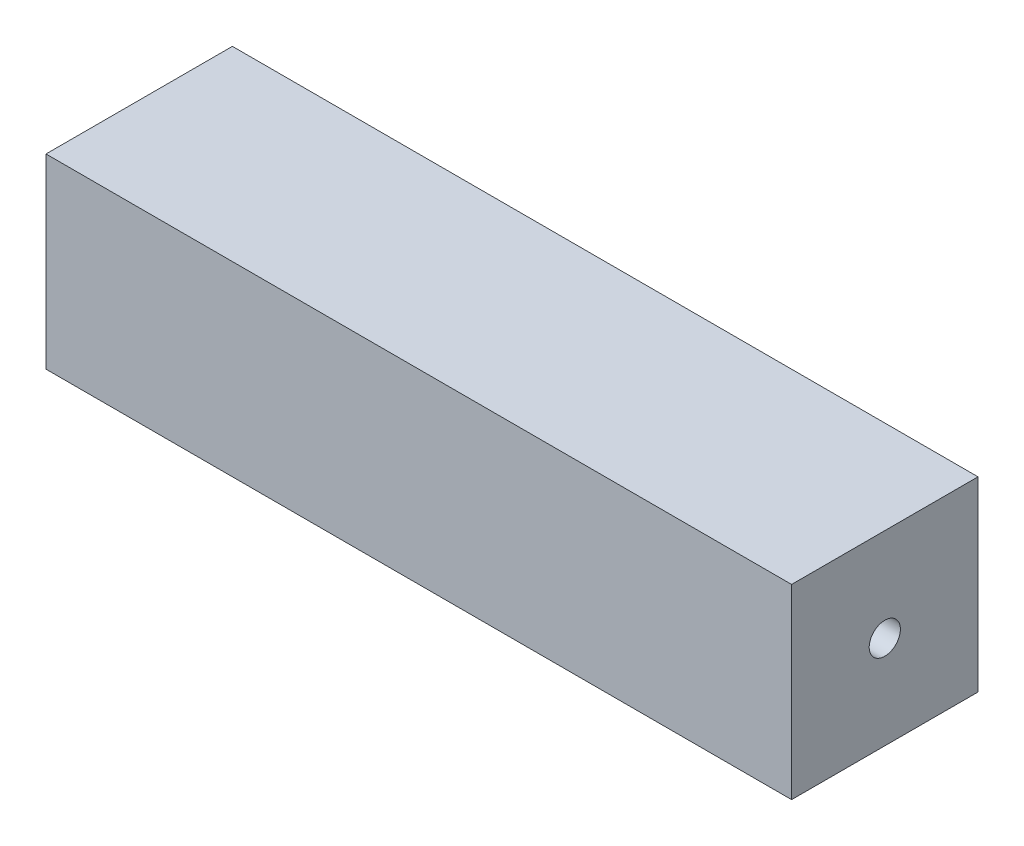
SolidWorks part; units mm, degrees
ref_plane "Front Plane" through (0, 0, 0) normal (0, 0, 1) x (1, 0, 0)
ref_plane "Top Plane" through (0, 0, 0) normal (0, 1, 0) x (1, 0, 0)
ref_plane "Right Plane" through (0, 0, 0) normal (1, 0, 0) x (0, 0, -1)
sketch "Sketch1" plane through (0, 0, 0) normal (0, 1, 0) x (1, 0, 0)
  line L1 (0, 0) -> (80, 0)
  line L2 (0, 0) -> (0, 20)
  line L3 (0, 20) -> (80, 20)
  line L4 (80, 0) -> (80, 20)
  dimension "D1" = 20
  dimension "D2" = 80
extrude "Boss-Extrude1" add sketch "Sketch1" along normal blind 20
sketch "Sketch2" plane through (80, 0, 0) normal (1, 0, 0) x (0, 0, -1)
  line L0 (0, 20) -> (20, 0) construction
  circle A0 centre (10, 10) radius 1.6727
  point P6 (10, 10)
extrude "Cut-Extrude1" cut sketch "Sketch2" against normal blind 20 contours A0
